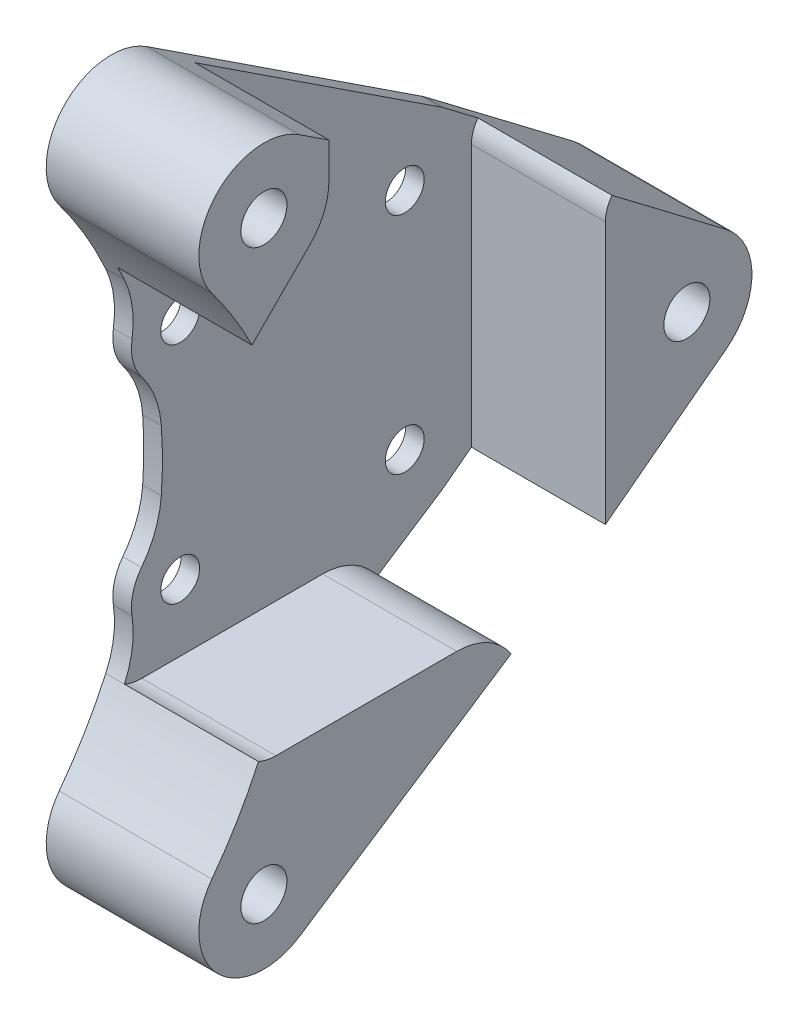
SolidWorks part; units mm, degrees
material "ABS"
ref_plane "Front" through (0, 0, 0) normal (0, 0, 1) x (1, 0, 0)
ref_plane "Top" through (0, 0, 0) normal (0, 1, 0) x (1, 0, 0)
ref_plane "Right" through (0, 0, 0) normal (1, 0, 0) x (0, 0, -1)
sketch "Sketch1" plane through (0, 0, 0) normal (1, 0, 0) x (0, 0, -1)
  line L34 (-12.3904, -33.8835) -> (14.4447, -16.2686)
  line L35 (14.7971, -16.0198) -> (29.2497, -5.0597)
  line L36 (29.2497, 5.0597) -> (14.7971, 16.0198)
  line L37 (14.4447, 16.2686) -> (-12.3904, 33.8835)
  line L38 (-12.3904, -33.8835) -> (14.4447, -16.2686)
  line L40 (14.7971, -16.0198) -> (29.2497, -5.0597)
  line L41 (29.2497, 5.0597) -> (14.7971, 16.0198)
  line L42 (14.4447, 16.2686) -> (-12.3904, 33.8835)
  arc A36 (-12.3904, 33.8835) -> (-20.955, 24.765) centre (-15.875, 28.575) ccw
  arc A37 (-16.4091, 17.1005) -> (-20.955, 24.765) centre (-53.975, 0) ccw
  arc A38 (-20.955, -24.765) -> (-12.3904, -33.8835) centre (-15.875, -28.575) ccw
  arc A39 (14.4447, -16.2686) -> (14.7971, -16.0198) centre (10.9601, -10.9601) ccw
  arc A42 (29.2497, -5.0597) -> (29.2497, 5.0597) centre (25.4127, 0) ccw
  arc A45 (14.7971, 16.0198) -> (14.4447, 16.2686) centre (10.9601, 10.9601) ccw
  arc A46 (-12.3904, 33.8835) -> (-20.955, 24.765) centre (-15.875, 28.575) ccw
  arc A47 (-16.4091, 17.1005) -> (-20.955, 24.765) centre (-53.975, 0) ccw
  arc A48 (-20.955, -24.765) -> (-12.3904, -33.8835) centre (-15.875, -28.575) ccw
  arc A49 (14.4447, -16.2686) -> (14.7971, -16.0198) centre (10.9601, -10.9601) ccw
  arc A50 (29.2497, -5.0597) -> (29.2497, 5.0597) centre (25.4127, 0) ccw
  arc A51 (14.7971, 16.0198) -> (14.4447, 16.2686) centre (10.9601, 10.9601) ccw
  arc A86 (-20.955, -24.765) -> (-16.4091, -17.1005) centre (-53.975, 0) ccw
  arc A87 (-20.955, -24.765) -> (-16.4091, -17.1005) centre (-53.975, 0) ccw
  arc A88 (-16.4091, -17.1005) -> (-15.6661, -11.6915) centre (-25.0781, -13.1542) ccw
  arc A89 (-16.4091, -17.1005) -> (-15.6661, -11.6915) centre (-25.0781, -13.1542) ccw
  arc A90 (-14.7423, -8.0659) -> (-15.6661, -11.6915) centre (-10.9601, -10.9601) ccw
  arc A91 (-14.7423, -8.0659) -> (-15.6661, -11.6915) centre (-10.9601, -10.9601) ccw
  arc A92 (-14.7423, -8.0659) -> (-12.8063, -2.9609) centre (-22.3068, -2.2776) ccw
  arc A93 (-14.7423, -8.0659) -> (-12.8063, -2.9609) centre (-22.3068, -2.2776) ccw
  arc A94 (-12.8063, -2.9609) -> (-12.8063, 2.9609) centre (-53.975, 0) ccw
  arc A95 (-12.8063, -2.9609) -> (-12.8063, 2.9609) centre (-53.975, 0) ccw
  arc A96 (-12.8063, 2.9609) -> (-14.7423, 8.0659) centre (-22.3068, 2.2776) ccw
  arc A97 (-12.8063, 2.9609) -> (-14.7423, 8.0659) centre (-22.3068, 2.2776) ccw
  arc A98 (-15.6661, 11.6915) -> (-14.7423, 8.0659) centre (-10.9601, 10.9601) ccw
  arc A99 (-15.6661, 11.6915) -> (-14.7423, 8.0659) centre (-10.9601, 10.9601) ccw
  arc A100 (-15.6661, 11.6915) -> (-16.4091, 17.1005) centre (-25.0781, 13.1542) ccw
  arc A101 (-15.6661, 11.6915) -> (-16.4091, 17.1005) centre (-25.0781, 13.1542) ccw
  dimension "D1" = 0
extrude "Boss-Extrude1" add sketch "Sketch1" along normal up to surface (14.9034 mm away)
hole_wizard "#8 Clearance Hole1" positions "Sketch2" profile "Sketch3" hole size "#8" standard "ANSI Inch" end condition through all
sketch "Sketch2" plane through (14.9034, 0, 0) normal (1, 0, 0) x (0, 0, -1)
  point P0 (-15.875, -28.575)
  point P4 (-15.875, 28.575)
  point P14 (25.4127, 0)
sketch "Sketch3" plane through (14.9034, -28.575, 15.875) normal (0, 1, 0) x (0, 0, -1)
  line L0 (0, 0) -> (0, 14.9034)
  line L1 (0, 14.9034) -> (2.2479, 14.9034)
  line L2 (2.2479, 14.9034) -> (2.2479, 0)
  line L5 (2.2479, 0) -> (0, 0)
  line L11 (0, -6.35) -> (0, 107.95) construction
  dimension "Thru Hole Dia." = 4.4958
  dimension "Thru Hole Depth" = 14.9034
sketch "Sketch4" plane through (14.9034, 0, 0) normal (1, 0, 0) x (0, 0, -1)
  line L0 (29.2497, 5.0597) -> (14.7971, 16.0198) construction
  line L1 (2.9521, -17.4625) -> (-14.7035, -17.4625)
  line L2 (17.4625, -17.4625) -> (17.4625, 11.5907)
  line L4 (-18.9, -13.266) -> (-18.9, 16.5697)
  line L5 (17.4625, 20.9064) -> (22.4103, 14.2247)
  line L6 (-15.725, 3.5) -> (-15.725, -3.5) construction
  line L7 (17.4625, 20.9064) -> (17.4625, 39.0857)
  line L8 (15.875, 6.5) -> (15.875, 11.8666) construction
  line L9 (-3.5, -15.875) -> (3.5, -15.875) construction
  line L10 (-53.975, 0) -> (-16.4091, -17.1005) construction
  line L11 (-18.9, 16.5697) -> (-11.3849, 24.0849)
  line L12 (-9.525, 28.575) -> (-9.525, 39.0857)
  line L13 (-9.525, 39.0857) -> (17.4625, 39.0857)
  line L14 (-12.3904, -33.8835) -> (14.4447, -16.2686) construction
  line L15 (7.6165, -28.1213) -> (17.4625, -17.4625)
  arc A0 (-11.3849, 24.0849) -> (-9.525, 28.575) centre (-15.875, 28.575) ccw
  arc A1 (-12.0684, 33.6575) -> (-19.6941, 33.6482) centre (-15.875, 28.575) ccw construction
  arc A3 (22.4103, 14.2247) -> (17.4625, 11.5907) centre (20.6375, 11.5907) ccw
  arc A5 (7.6165, -28.1213) -> (2.9521, -17.4625) centre (2.9521, -23.8125) ccw
  arc A7 (-18.9, -13.266) -> (-14.7035, -17.4625) centre (-14.7035, -13.266) ccw
  arc A9 (-16.4091, -17.1005) -> (-15.6661, -11.6915) centre (-25.0781, -13.1542) ccw construction
  arc A11 (-20.955, -24.765) -> (-16.4091, -17.1005) centre (-53.975, 0) ccw construction
  dimension "D6" = 6.35
  dimension "D7" = 6.35
  dimension "D1" = 3.175
  dimension "D2" = 45
  dimension "D3" = 1.5875
  dimension "D4" = 1.5875
extrude "Cut-Extrude1" cut sketch "Sketch4" against normal up to surface (13.0842 mm away)
hole_wizard "#6 Clearance Hole1" positions "Sketch5" profile "Sketch6" hole size "#6" standard "ANSI Inch" end condition through all
sketch "Sketch5" plane through (0, 0, 0) normal (-1, 0, 0) x (0, 0, 1)
  circle A0 centre (-10.9601, 10.9601) radius 1.8986 construction
  circle A1 centre (-10.9601, -10.9601) radius 1.8986 construction
  circle A2 centre (10.9601, -10.9601) radius 1.8986 construction
  point P0 (10.9601, -10.9601)
  point P2 (-10.9601, -10.9601)
  point P4 (-10.9601, 10.9601)
  point P6 (10.9601, 10.9601)
sketch "Sketch6" plane through (0, -10.9601, 10.9601) normal (0, 1, 0) x (0, 0, 1)
  line L0 (0, 0) -> (0, 14.9034)
  line L1 (0, 14.9034) -> (1.8986, 14.9034)
  line L2 (1.8986, 14.9034) -> (1.8986, 0)
  line L5 (1.8986, 0) -> (0, 0)
  line L11 (0, -6.35) -> (0, 107.95) construction
  dimension "Thru Hole Dia." = 3.7973
  dimension "Thru Hole Depth" = 14.9034
ref_plane "Plane1" through (14.9034, 18.4277, 17.042) normal (-1, 0, 0) x (0, 0, 1)
